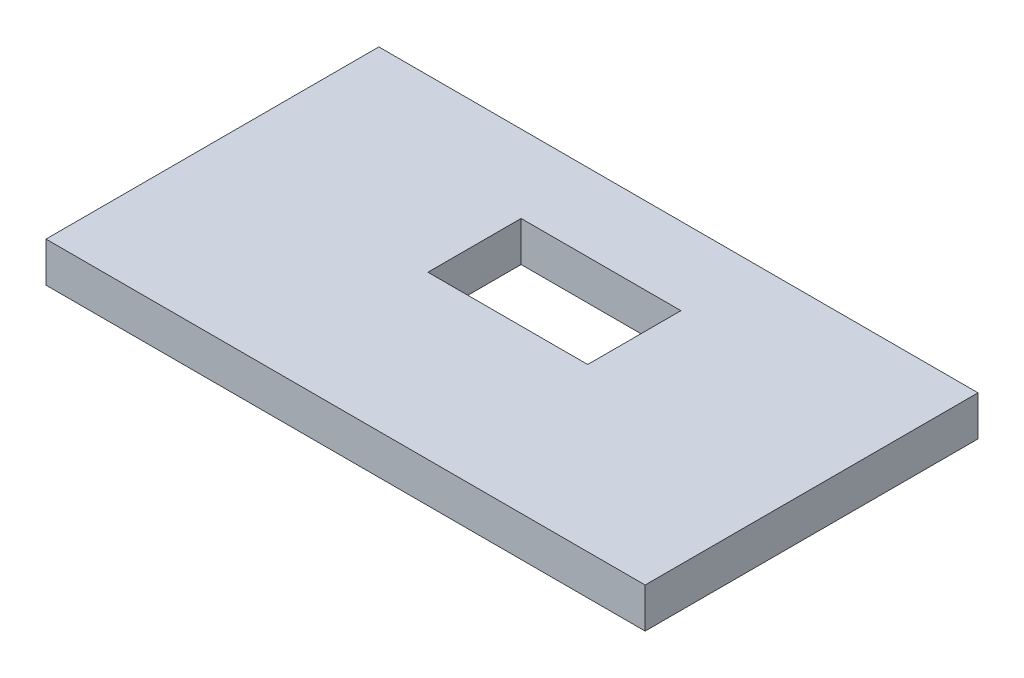
SolidWorks part; units mm, degrees
ref_plane "Front Plane" through (0, 0, 0) normal (0, 0, 1) x (1, 0, 0)
ref_plane "Top Plane" through (0, 0, 0) normal (0, 1, 0) x (1, 0, 0)
ref_plane "Right Plane" through (0, 0, 0) normal (1, 0, 0) x (0, 0, -1)
sketch "Sketch1" plane through (0, 0, 0) normal (0, 1, 0) x (1, 0, 0)
  line L1 (0, 0) -> (45, 0)
  line L2 (0, 0) -> (0, 25)
  line L3 (0, 25) -> (45, 25)
  line L4 (45, 0) -> (45, 25)
  dimension "D1" = 45
  dimension "D2" = 25
extrude "Boss-Extrude1" add sketch "Sketch1" along normal blind 3
sketch "Sketch2" plane through (0, 0, 0) normal (0, -1, 0) x (1, 0, 0)
  line L1 (16.5, -19.1848) -> (28.5, -19.1848)
  line L2 (16.5, -19.1848) -> (16.5, -12.1848)
  line L3 (16.5, -12.1848) -> (28.5, -12.1848)
  line L4 (28.5, -19.1848) -> (28.5, -12.1848)
  line L5 (45, 0) -> (45, -25) construction
  dimension "D1" = 12
  dimension "D2" = 7
  dimension "D3" = 16.5
extrude "Cut-Extrude1" cut sketch "Sketch2" against normal blind 3
